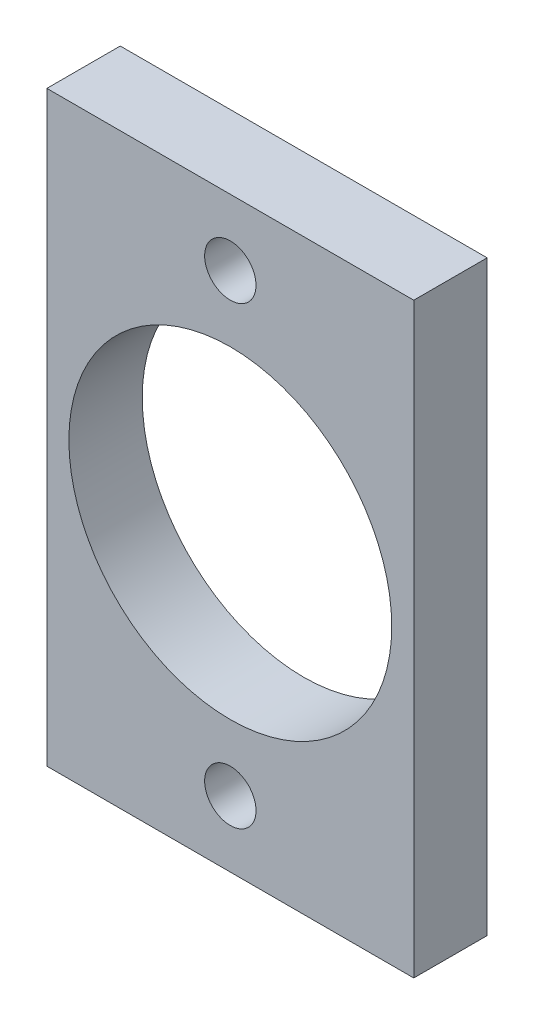
SolidWorks part; units mm, degrees
ref_plane "Front Plane" through (0, 0, 0) normal (0, 0, 1) x (1, 0, 0)
ref_plane "Top Plane" through (0, 0, 0) normal (0, 1, 0) x (1, 0, 0)
ref_plane "Right Plane" through (0, 0, 0) normal (1, 0, 0) x (0, 0, -1)
sketch "Sketch1" plane through (0, 0, 0) normal (0, 0, 1) x (1, 0, 0)
  line L0 (44.4156, 335) -> (44.4156, 25) construction
  line L1 (19.4156, 335) -> (44.4156, 335)
  line L2 (19.4156, 335) -> (19.4156, 295)
  line L3 (19.4156, 295) -> (44.4156, 295)
  line L4 (44.4156, 335) -> (44.4156, 295)
  line L5 (19.4156, 335) -> (44.4156, 295) construction
  line L6 (44.4156, 335) -> (19.4156, 295) construction
  line L7 (31.9156, 295) -> (31.9156, 304) construction
  line L8 (31.9156, 335) -> (31.9156, 326) construction
  circle A0 centre (31.9156, 315) radius 11
  circle A1 centre (31.9156, 330.5) radius 1.75
  circle A2 centre (31.9156, 299.5) radius 1.75
  point P15 (31.9156, 299.5)
  dimension "D1" = 22
  dimension "D3" = 3.5
  dimension "D4" = 3.5
  dimension "D2" = 40
extrude "Boss-Extrude1" add sketch "Sketch1" along normal blind 5
